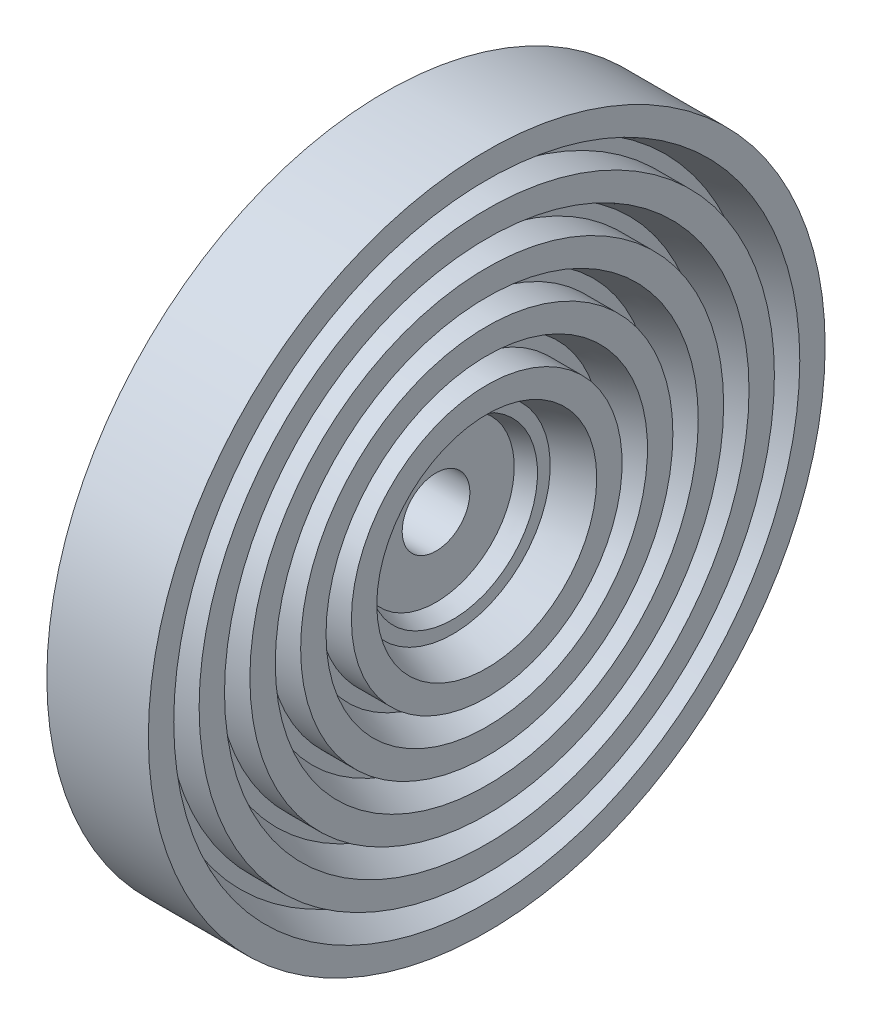
SolidWorks part; units mm, degrees
material "Gomma"
ref_plane "Piano frontale" through (0, 0, 0) normal (0, 0, 1) x (1, 0, 0)
ref_plane "Piano superiore" through (0, 0, 0) normal (0, 1, 0) x (1, 0, 0)
ref_plane "Piano destro" through (0, 0, 0) normal (1, 0, 0) x (0, 0, -1)
sketch "Schizzo3" plane through (0, 0, 0) normal (0, 0, 1) x (1, 0, 0)
  line L0 (0, 0) -> (0, 18)
  line L1 (0, 18) -> (6, 18)
  line L4 (4, 15) -> (4, 15.75)
  line L7 (6, 12) -> (4, 12)
  line L8 (4, 12) -> (4, 12.75)
  line L13 (4, 9) -> (6, 9)
  line L14 (6, 9) -> (6, 7.5)
  line L16 (4, 6.75) -> (4, 6)
  line L17 (4, 6) -> (6, 6)
  line L18 (6, 6) -> (6, 4.5)
  line L20 (4, 3.75) -> (4, 3)
  line L22 (3, 2.625) -> (3, 0)
  line L23 (3, 0) -> (0, 0)
  line L24 (4, 9) -> (4, 9.75)
  line L26 (6, 10.5) -> (6, 12)
  line L27 (4, 15) -> (6, 15)
  line L28 (6, 15) -> (6, 13.5)
  line L30 (6, 16.5) -> (6, 18)
  line L31 (-0.6644, -2) -> (15.628, -2) construction
  line L32 (6, 16.5) -> (4, 15.75)
  line L33 (6, 13.5) -> (4, 12.75)
  line L34 (6, 10.5) -> (4, 9.75)
  line L35 (6, 7.5) -> (4, 6.75)
  line L36 (6, 4.5) -> (4, 3.75)
  line L37 (4, 3) -> (3, 2.625)
  dimension "D1" = 3
  dimension "D2" = 6
  dimension "D3" = 4
  dimension "D4" = 18
  dimension "D5" = 1.5
  dimension "D7" = 1.5
  dimension "D9" = 1.5
  dimension "D11" = 1.5
  dimension "D12" = 1.5
  dimension "D15" = 2
revolve "Rivoluzione1" add sketch "Schizzo3" angle 360 about L31
